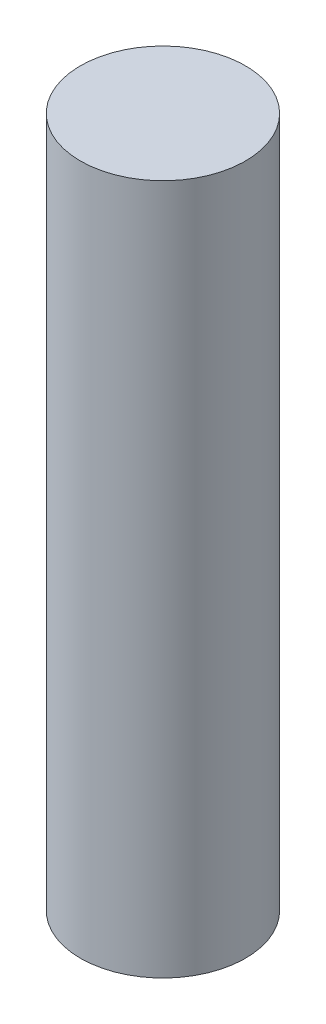
SolidWorks part; units mm, degrees
material "Copper"
ref_plane "Front Plane" through (0, 0, 0) normal (0, 0, 1) x (1, 0, 0)
ref_plane "Top Plane" through (0, 0, 0) normal (0, 1, 0) x (1, 0, 0)
ref_plane "Right Plane" through (0, 0, 0) normal (1, 0, 0) x (0, 0, -1)
sketch "Sketch1" plane through (0, 0, 0) normal (0, 1, 0) x (1, 0, 0)
  circle A0 centre (0, 0) radius 30
  dimension "D1" = 60
extrude "Boss-Extrude1" add sketch "Sketch1" along normal blind 251 contours A0
